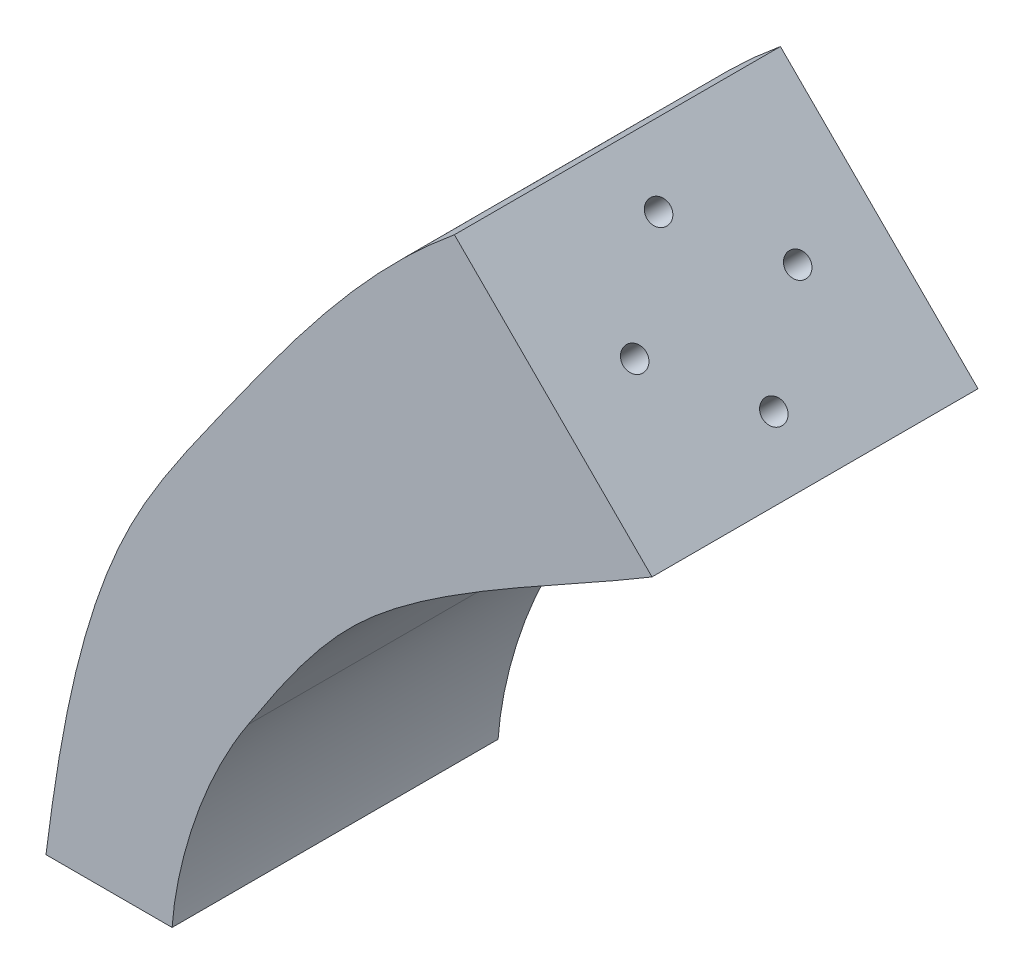
SolidWorks part; units mm, degrees
material "ABS"
ref_plane "Front Plane" through (0, 0, 0) normal (0, 0, 1) x (1, 0, 0)
ref_plane "Top Plane" through (0, 0, 0) normal (0, 1, 0) x (1, 0, 0)
ref_plane "Right Plane" through (0, 0, 0) normal (1, 0, 0) x (0, 0, -1)
sketch "Sketch1" plane through (0, 0, 0) normal (0, 0, 1) x (1, 0, 0)
  line L0 (2.0914, 20.6619) -> (19.062, 3.6913)
  line L1 (-32.9879, -42.9928) -> (-22.1583, -42.9928)
  spline S0 degree 3 poles (2.0914, 20.6619) (-6.1531, 13.9026) (-14.8859, 1.6142) (-29.2947, -18.7757) (-31.7978, -33.5362) (-32.9879, -42.9928) knots 0 0 0 0 0.424008 0.607839 1 1 1 1
  spline S1 degree 3 poles (19.062, 3.6913) (12.7462, -0.1094) (3.6901, -4.556) (-8.4727, -13.7663) (-12.8795, -20.3951) (-15.6286, -24.6339) knots 0 0 0 0 0.486352 0.663537 1 1 1 1
  spline S2 degree 3 poles (-15.6286, -24.6339) (-20.1398, -31.5111) (-21.8926, -38.9284) (-22.1583, -42.9928) knots 0 0 0 0 1 1 1 1
  dimension "D1" = 24
extrude "Boss-Extrude1" add sketch "Sketch1" along normal blind 28
sketch "Sketch2" plane through (11.3766, 11.3766, 0) normal (0.7071, 0.7071, 0) x (0, 0, -1)
  line L1 (-28, 13.1313) -> (0, 13.1313) construction
  line L2 (-28, -10.8687) -> (0, -10.8687) construction
  circle A0 centre (-7, 1.1313) radius 1
  circle A1 centre (-14, 8.1313) radius 1
  circle A2 centre (-14, -5.8687) radius 1
  circle A3 centre (-21, 1.1313) radius 1
  dimension "D1" = 1
  dimension "D2" = 2
  dimension "D3" = 1
  dimension "D4" = 2
  dimension "D5" = 12
  dimension "D6" = 5
  dimension "D7" = 5
extrude "Cut-Extrude1" cut sketch "Sketch2" against normal blind 8
